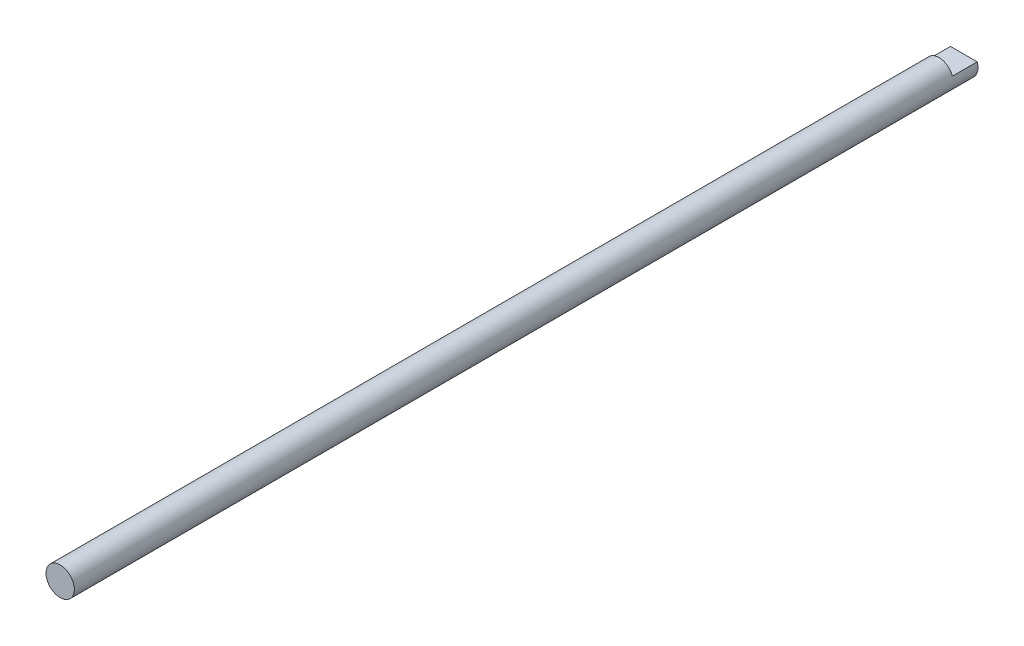
SolidWorks part; units mm, degrees
ref_plane "Front Plane" through (0, 0, 0) normal (0, 0, 1) x (1, 0, 0)
ref_plane "Top Plane" through (0, 0, 0) normal (0, 1, 0) x (1, 0, 0)
ref_plane "Right Plane" through (0, 0, 0) normal (1, 0, 0) x (0, 0, -1)
sketch "Sketch1" plane through (0, 0, 0) normal (0, 0, 1) x (1, 0, 0)
  circle A0 centre (0, 0) radius 4
  dimension "D1" = 8
extrude "Boss-Extrude1" add sketch "Sketch1" along normal blind 255
sketch "Sketch2" plane through (0, 0, 255) normal (0, 0, 1) x (1, 0, 0)
  line L0 (0, 4) -> (0, 1.3333) construction
  line L1 (0, 1.3333) -> (0, -1.3333) construction
  line L2 (0, -1.3333) -> (0, -4) construction
  line L3 (-3.7712, 1.3333) -> (3.7712, 1.3333)
  line L4 (3.7712, 1.3333) -> (7.7227, 6.8869)
  line L5 (7.7227, 6.8869) -> (-8.2193, 6.8869)
  line L6 (-8.2193, 6.8869) -> (-3.7712, 1.3333)
  circle A0 centre (0, 0) radius 4 construction
extrude "Cut-Extrude1" cut sketch "Sketch2" along normal blind 7 from surface at -255 starting at face at (4, 0, 0)
